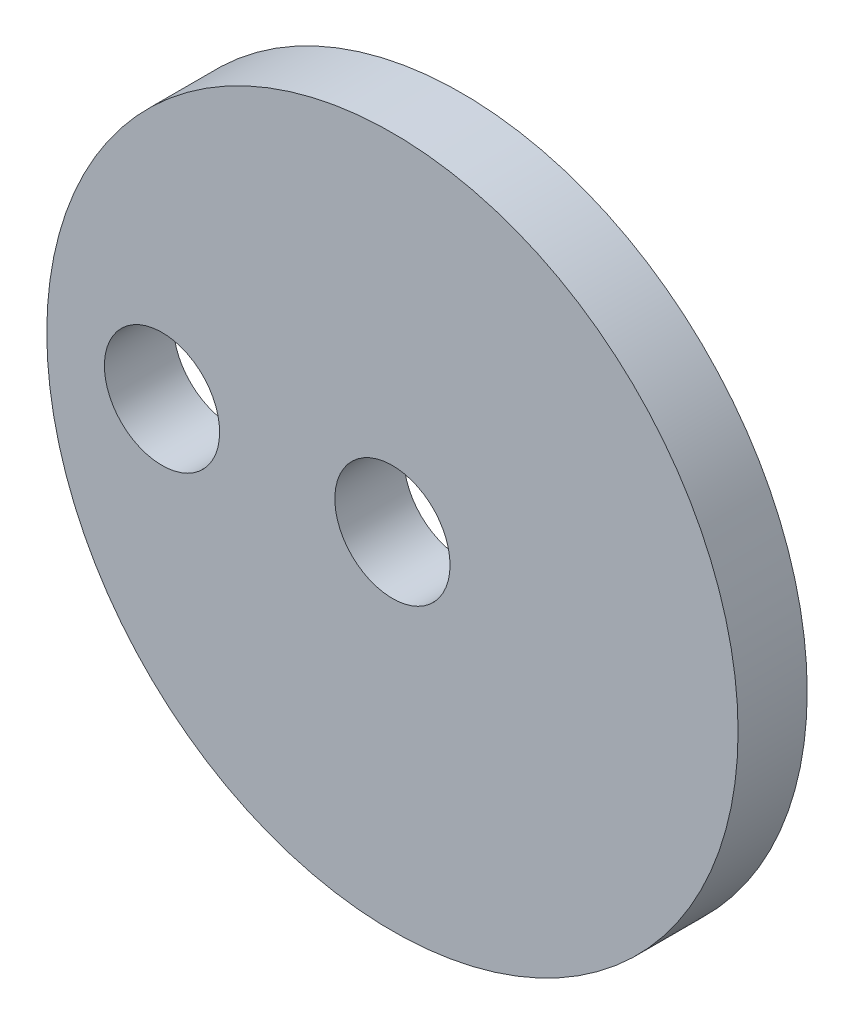
SolidWorks part; units mm, degrees
ref_plane "Front Plane" through (0, 0, 0) normal (0, 0, 1) x (1, 0, 0)
ref_plane "Top Plane" through (0, 0, 0) normal (0, 1, 0) x (1, 0, 0)
ref_plane "Right Plane" through (0, 0, 0) normal (1, 0, 0) x (0, 0, -1)
sketch "Sketch1" plane through (0, 0, 0) normal (0, 0, 1) x (1, 0, 0)
  circle A0 centre (0, 0) radius 15
  dimension "D1" = 30
extrude "Boss-Extrude1" add sketch "Sketch1" along normal blind 3
sketch "Sketch2" plane through (0, 0, 3) normal (0, 0, 1) x (1, 0, 0)
  circle A0 centre (0, 0) radius 2.5
  circle A1 centre (-10, 0) radius 2.5
  dimension "D1" = 5
  dimension "D2" = 5
  dimension "D3" = 10
extrude "Cut-Extrude1" cut sketch "Sketch2" against normal blind 3
equation "\"gear_d\"= 30"
equation "\"D1@Sketch1\"=\"gear_d\""
equation "\"gear_thickness\"=3"
equation "\"D1@Boss-Extrude1\"=\"gear_thickness\""
equation "\"pin_d\"=5"
equation "\"D1@Sketch2\"=\"pin_d\""
equation "\"D2@Sketch2\"= \"pin_d\""
equation "\"D3@Sketch2\"= \"pin_d\"*2"
equation "\"D1@Cut-Extrude1\"= \"gear_thickness\""
